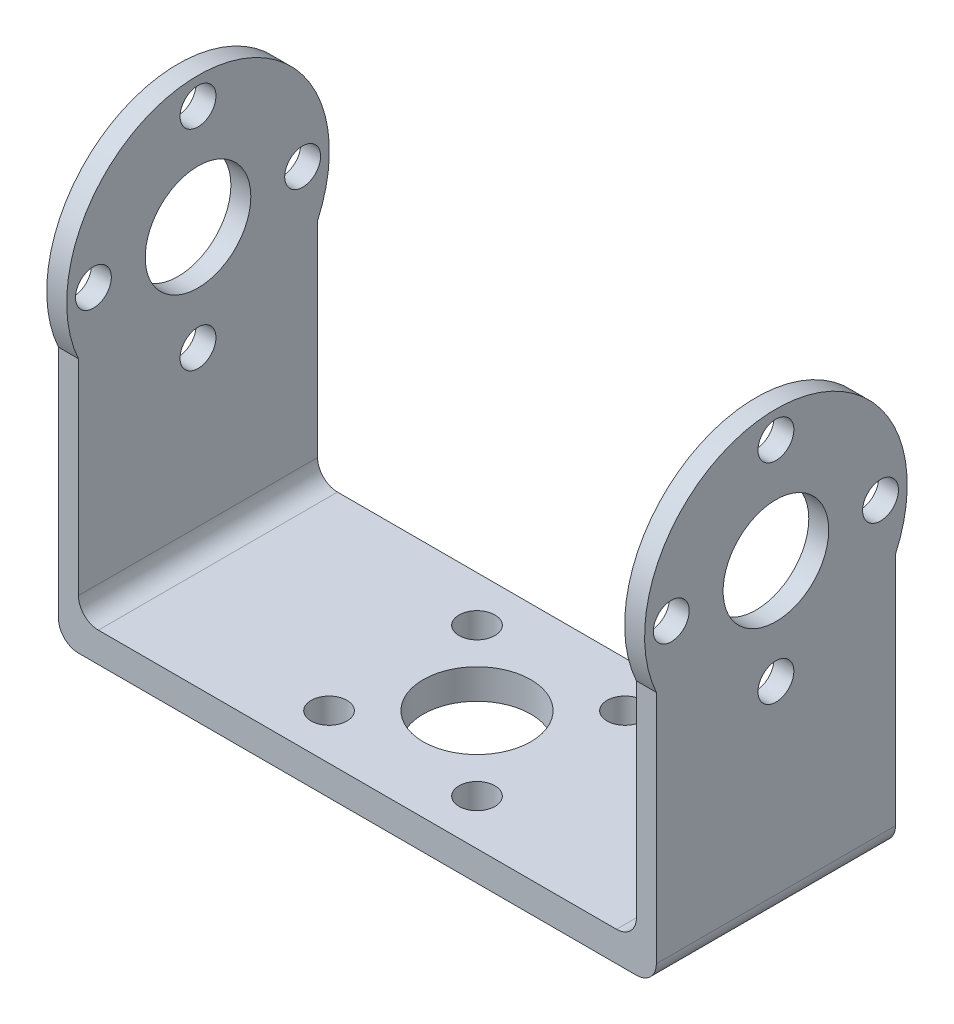
SolidWorks part; units mm, degrees
ref_plane "Alzado" through (0, 0, 0) normal (0, 0, 1) x (1, 0, 0)
ref_plane "Planta" through (0, 0, 0) normal (0, 1, 0) x (1, 0, 0)
ref_plane "Vista lateral" through (0, 0, 0) normal (1, 0, 0) x (0, 0, -1)
sketch "Croquis1" plane through (0, 0, 0) normal (0, 1, 0) x (1, 0, 0)
  line L1 (-30, 12) -> (30, 12)
  line L2 (-30, 12) -> (-30, -12)
  line L3 (-30, -12) -> (30, -12)
  line L4 (30, 12) -> (30, -12)
  line L5 (-30, 12) -> (30, -12) construction
  line L6 (-30, -12) -> (30, 12) construction
  point P0 (0, 0)
  dimension "D1" = 60
  dimension "D2" = 24
extrude "Saliente-Extruir1" add sketch "Croquis1" along normal blind 2
ref_plane "Plano1" through (30, 0, 0) normal (1, 0, 0) x (0, 0, -1)
sketch "Croquis3" plane through (30, 0, 0) normal (1, 0, 0) x (0, 0, -1)
  line L0 (-12, 2) -> (12, 2) construction
  line L1 (12, 2) -> (-12, 2)
  line L2 (12, 2) -> (12, 24.5891)
  line L3 (12, 30.04) -> (-12, 30.04) construction
  line L4 (-12, 2) -> (-12, 24.5891)
  line L5 (-12, 0) -> (12, 0) construction
  line L6 (-12, 24.5891) -> (-12, 30.04) construction
  line L7 (12, 24.5891) -> (12, 30.04) construction
  arc A0 (12, 24.5891) -> (-12, 24.5891) centre (0, 30.04) ccw
  circle A1 centre (0, 30.04) radius 5.3
  dimension "D1" = 10.6
  dimension "D3" = 26.36
  dimension "D2" = 30.04
extrude "Saliente-Extruir2" add sketch "Croquis3" against normal blind 2
sketch "Croquis5" plane through (30, 0, 0) normal (1, 0, 0) x (0, 0, -1)
  line L0 (0, 30.04) -> (0, 40.54) construction
  circle A0 centre (0, 30.04) radius 10.5 construction
  circle A1 centre (0, 40.54) radius 1.8
  circle A2 centre (10.5, 30.04) radius 1.8
  circle A3 centre (0, 19.54) radius 1.8
  circle A4 centre (-10.5, 30.04) radius 1.8
  point P14 (0, 30.04)
  dimension "D1" = 21
  dimension "D2" = 3.6
  dimension "D3" = 4
extrude "Cortar-Extruir1" cut sketch "Croquis5" against normal up to next
mirror "Simetría1" about plane through (0, 0, 0) normal (1, 0, 0) of "Saliente-Extruir2", "Cortar-Extruir1"
sketch "Croquis6" plane through (0, 0, 0) normal (0, -1, 0) x (1, 0, 0)
  line L1 (-30, 12) -> (30, 12)
  line L2 (-30, 12) -> (-30, -12)
  line L3 (-30, -12) -> (30, -12)
  line L4 (30, 12) -> (30, -12)
extrude "Saliente-Extruir3" add sketch "Croquis6" along normal blind 1
sketch "Croquis7" plane through (0, -1, 0) normal (0, -1, 0) x (1, 0, 0)
  line L0 (0, 0) -> (7.4246, -7.4246) construction
  line L1 (0, 0) -> (10.5, 0) construction
  circle A0 centre (0, 0) radius 5.4
  circle A1 centre (0, 0) radius 10.5 construction
  circle A2 centre (7.4246, -7.4246) radius 1.8
  circle A3 centre (-7.4236, -7.4236) radius 1.8
  circle A4 centre (-7.4226, 7.4246) radius 1.8
  circle A5 centre (7.4256, 7.4236) radius 1.8
  point P16 (0.001, 0)
  dimension "D2" = 3.6
  dimension "D3" = 10.8
  dimension "D5" = 21
  dimension "D1" = 45
  dimension "D4" = 4
extrude "Cortar-Extruir2" cut sketch "Croquis7" against normal up to next
fillet "Redondeo1" radius 2 4 edges at (-28, 2, 0) (-30, -1, 0) (30, -1, 0)
